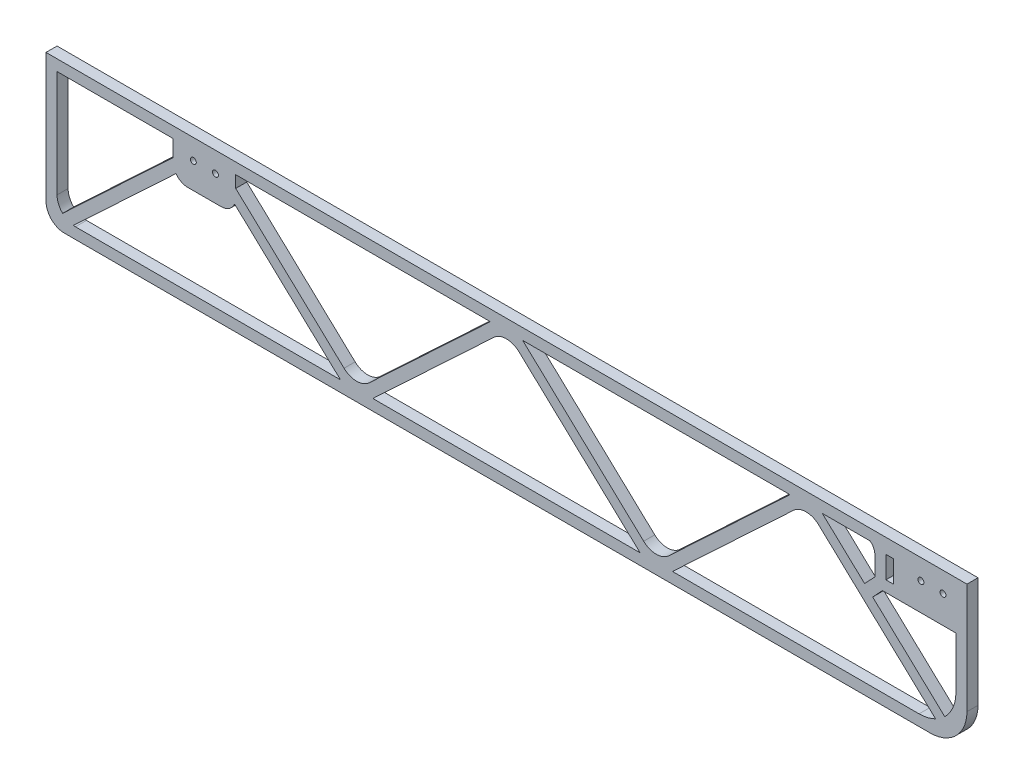
SolidWorks part; units mm, degrees
material "轻木"
ref_plane "前视基准面" through (0, 0, 0) normal (0, 0, 1) x (1, 0, 0)
ref_plane "上视基准面" through (0, 0, 0) normal (0, 1, 0) x (1, 0, 0)
ref_plane "右视基准面" through (0, 0, 0) normal (1, 0, 0) x (0, 0, -1)
other "Configuration Table"
sketch "草图1" plane through (0, 0, 0) normal (0, 0, 1) x (1, 0, 0)
  line L1 (-125, 20) -> (125, 20)
  line L2 (-125, 20) -> (-125, -15)
  line L3 (-120, -20) -> (115, -20)
  line L4 (125, 20) -> (125, -10)
  line L5 (-125, 20) -> (125, -20) construction
  line L6 (-125, -20) -> (125, 20) construction
  line L10 (-122, -17) -> (-85.7205, 17)
  line L11 (-117.6128, -17) -> (-81.3333, 17)
  line L12 (-76.9462, 17) -> (-44.0857, -13.7958)
  line L13 (-81.3333, 17) -> (-45.0538, -17)
  line L14 (-36.2795, -17) -> (-3.4191, 13.7958)
  line L15 (-37.2476, -13.7958) -> (-4.3872, 17)
  line L16 (0, 0) -> (0, -16) construction
  line L17 (36.2795, -17) -> (3.4191, 13.7958)
  line L18 (37.2476, -13.7958) -> (4.3872, 17)
  line L19 (76.9462, 17) -> (44.0857, -13.7958)
  line L20 (77.9143, 13.7958) -> (45.0538, -17)
  line L21 (117.6128, -17) -> (84.7524, 13.7958)
  line L22 (122, -17) -> (85.7205, 17)
  line L23 (-125, 20) -> (-125, -20) construction
  line L28 (122, 17) -> (100, 17)
  line L29 (122, 17) -> (122, 7)
  line L34 (-122, 17) -> (-122, -12)
  line L35 (-117, -17) -> (112, -17)
  line L36 (122, 17) -> (122, -7)
  line L37 (-122, 17) -> (122, 17)
  line L38 (122, 7) -> (100, 7)
  line L39 (100, 17) -> (100, 7)
  line L52 (103, 16) -> (105, 16)
  line L53 (103, 16) -> (103, 10)
  line L54 (103, 10) -> (105, 10)
  line L55 (105, 16) -> (105, 10)
  line L56 (-125, -20) -> (125, -20) construction
  line L57 (125, 20) -> (125, -20) construction
  line L58 (-122, 17) -> (-122, -17) construction
  line L59 (-122, -17) -> (122, -17) construction
  line L60 (122, 17) -> (122, -17) construction
  line L61 (-90.5, 17) -> (-90.5, 11.5)
  line L62 (-86.5, 7.5) -> (-77.5, 7.5)
  line L63 (-73.5, 11.5) -> (-73.5, 17)
  line L64 (-73.5, 32.5) -> (-73.5, 10.5) construction
  line L65 (-90.5, 32.5) -> (-90.5, 10.5) construction
  line L66 (102.0558, 7) -> (99.4069, 4.1735)
  line L67 (100, 9.1936) -> (97.2179, 6.225)
  line L68 (-86, 13.5) -> (-84, 13.5) construction
  line L70 (-86, 29.5) -> (-86, 13.5) construction
  line L71 (-85, 14.5) -> (-79, 14.5) construction
  line L72 (-79, 14.5) -> (118.5, 14.5) construction
  arc A3 (-125, -15) -> (-120, -20) centre (-120, -15) ccw
  arc A5 (-122, -12) -> (-117, -17) centre (-117, -12) ccw
  arc A6 (112, -17) -> (122, -7) centre (112, -7) ccw
  arc A7 (-44.0857, -13.7958) -> (-37.2476, -13.7958) centre (-40.6667, -10.1475) ccw
  arc A8 (-3.4191, 13.7958) -> (3.4191, 13.7958) centre (0, 10.1475) cw
  arc A9 (37.2476, -13.7958) -> (44.0857, -13.7958) centre (40.6667, -10.1475) ccw
  arc A10 (77.9143, 13.7958) -> (84.7524, 13.7958) centre (81.3333, 10.1475) cw
  arc A11 (125, -10) -> (115, -20) centre (115, -10) cw
  arc A12 (-77.5, 7.5) -> (-73.5, 11.5) centre (-77.5, 11.5) ccw
  arc A13 (-90.5, 11.5) -> (-86.5, 7.5) centre (-86.5, 11.5) ccw
  arc A14 (100, 14.4064) -> (98.6878, 17) centre (96.7808, 14.4064) ccw
  circle A15 centre (-85, 14.5) radius 0.8
  circle A16 centre (-79, 14.5) radius 0.8
  circle A17 centre (118.5, 14.5) radius 0.8
  circle A18 centre (112.5, 14.5) radius 0.8
  point P0 (0, 0)
  point P46 (100, 7)
  point P69 (-40.6667, -17)
  point P73 (0, 17)
  point P76 (40.6667, -17)
  point P79 (81.3333, 17)
  dimension "D15" = 3
  dimension "D16" = 1.5
  dimension "D17" = 90
  dimension "D18" = 5
  dimension "D19" = 5
  dimension "D20" = 10
  dimension "D21" = 5
  dimension "D22" = 5
  dimension "D23" = 5
  dimension "D24" = 5
  dimension "D25" = 10
  dimension "D8" = 4
  dimension "D9" = 4
  dimension "D30" = 1.6
  dimension "D4" = 3
  dimension "D5" = 3
  dimension "D6" = 22
  dimension "D7" = 10
  dimension "D3" = 3
  dimension "D11" = 2
  dimension "D12" = 6
  dimension "D13" = 20
  dimension "D14" = 4
  dimension "D26" = 40
  dimension "D27" = 250
  dimension "D28" = 1
  dimension "D29" = 1
  dimension "D31" = 6
  dimension "D33" = 197.5
  dimension "D10" = 3
  dimension "D32" = 2
extrude "凸台-拉伸1" add sketch "草图1" along normal blind 3
